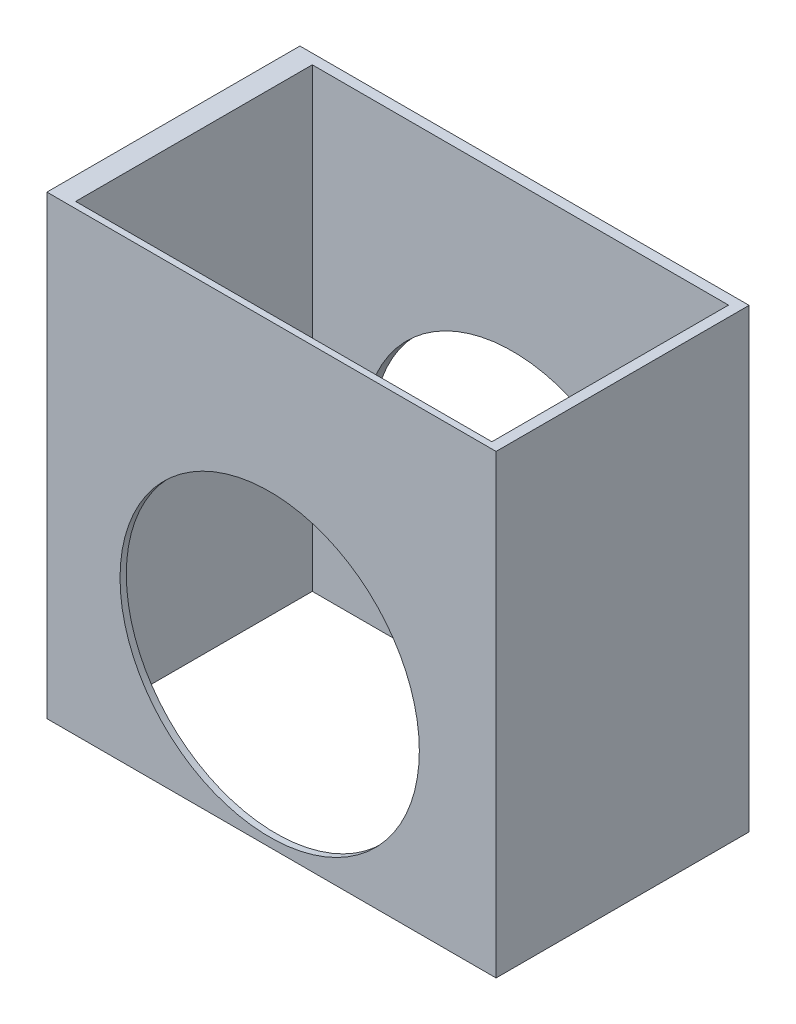
SolidWorks part; units mm, degrees
ref_plane "Front Plane" through (0, 0, 0) normal (0, 0, 1) x (1, 0, 0)
ref_plane "Top Plane" through (0, 0, 0) normal (0, 1, 0) x (1, 0, 0)
ref_plane "Right Plane" through (0, 0, 0) normal (1, 0, 0) x (0, 0, -1)
sketch "Sketch1" plane through (0, 0, 0) normal (0, 0, 1) x (1, 0, 0)
  line L1 (0, 0) -> (-23.899, 0)
  line L2 (0, 0) -> (0, 24.2638)
  line L3 (0, 24.2638) -> (-23.899, 24.2638)
  line L4 (-23.899, 0) -> (-23.899, 24.2638)
extrude "Boss-Extrude3" add sketch "Sketch1" along normal blind 13.462
sketch "Sketch2" plane through (0, 0, 13.462) normal (0, 0, 1) x (1, 0, 0)
  circle A0 centre (-12.046, 8.4305) radius 7.9624
extrude "Cut-Extrude1" cut sketch "Sketch2" against normal blind 35.56
sketch "Sketch3" plane through (0, 24.2638, 0) normal (0, 1, 0) x (1, 0, 0)
  line L5 (-22.7038, -0.5361) -> (-0.5583, -0.5361)
  line L6 (-22.7038, -0.5361) -> (-22.7038, -13.1277)
  line L7 (-22.7038, -13.1277) -> (-0.5583, -13.1277)
  line L8 (-0.5583, -0.5361) -> (-0.5583, -13.1277)
extrude "Cut-Extrude2" cut sketch "Sketch3" against normal blind 167.64
